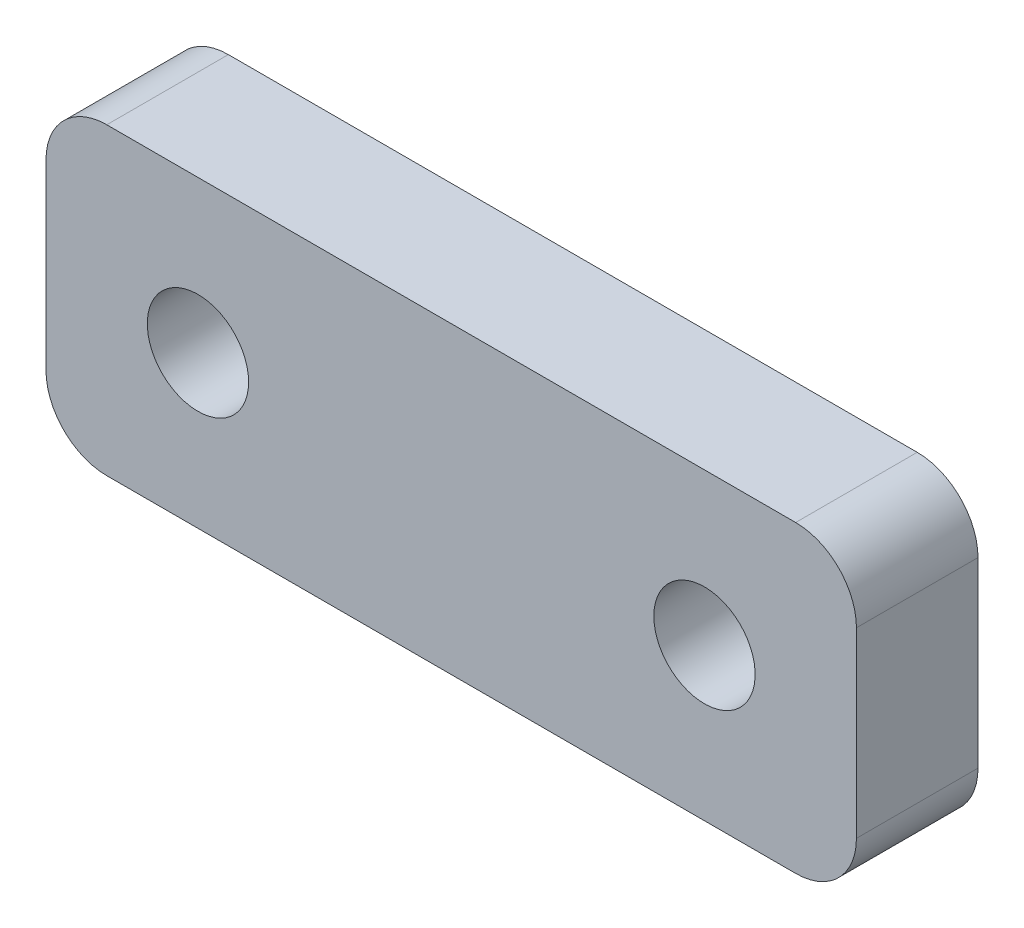
SolidWorks part; units mm, degrees
material "POM 乙缩醛共聚物"
ref_plane "前视基准面" through (0, 0, 0) normal (0, 0, 1) x (1, 0, 0)
ref_plane "上视基准面" through (0, 0, 0) normal (0, 1, 0) x (1, 0, 0)
ref_plane "右视基准面" through (0, 0, 0) normal (1, 0, 0) x (0, 0, -1)
sketch "草图1" plane through (0, 0, 0) normal (0, 0, 1) x (1, 0, 0)
  line L1 (-20, 7.5) -> (20, 7.5)
  line L2 (-20, 7.5) -> (-20, -7.5)
  line L3 (-20, -7.5) -> (20, -7.5)
  line L4 (20, 7.5) -> (20, -7.5)
  line L5 (-20, 7.5) -> (20, -7.5) construction
  line L6 (-20, -7.5) -> (20, 7.5) construction
  point P0 (0, 0)
  dimension "D1" = 40
  dimension "D2" = 15
extrude "凸台-拉伸1" add sketch "草图1" along normal blind 6
sketch "草图2" plane through (0, 0, 6) normal (0, 0, 1) x (1, 0, 0)
  line L0 (0, 7.5) -> (0, -7.5) construction
  line L1 (20, 7.5) -> (-20, 7.5) construction
  line L2 (-20, -7.5) -> (20, -7.5) construction
  line L3 (0, 0) -> (-12.5, 0) construction
  circle A0 centre (-12.5, 0) radius 2.5
  circle A1 centre (12.5, 0) radius 2.5
  dimension "D2" = 5
  dimension "D1" = 12.5
extrude "切除-拉伸1" cut sketch "草图2" against normal through all
fillet "圆角1" radius 3 4 edges at (20, 7.5, 3) (20, -7.5, 3) (-20, -7.5, 3) (-20, 7.5, 3)
